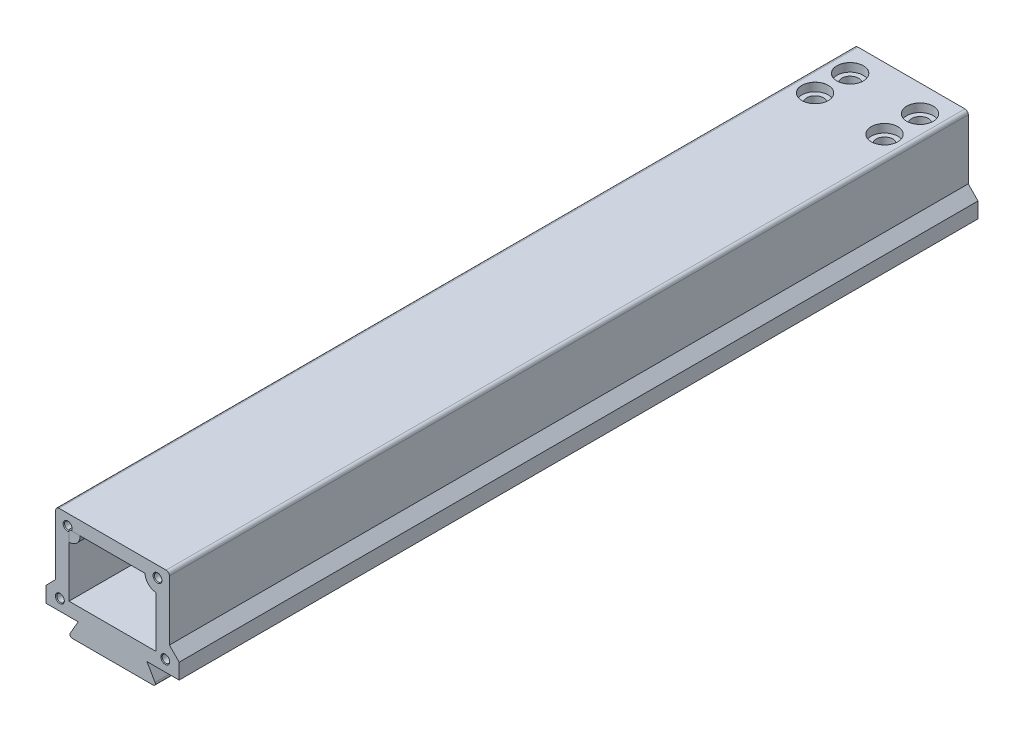
SolidWorks part; units mm, degrees
ref_plane "Front Plane" through (0, 0, 0) normal (0, 0, 1) x (1, 0, 0)
ref_plane "Top Plane" through (0, 0, 0) normal (0, 1, 0) x (1, 0, 0)
ref_plane "Right Plane" through (0, 0, 0) normal (1, 0, 0) x (0, 0, -1)
sketch "Sketch1" plane through (0, 0, 0) normal (0, 0, 1) x (1, 0, 0)
  line L0 (-39.9968, 0) -> (40, 0)
  line L1 (40, 0) -> (30.9933, 15.6)
  line L2 (30.9933, 15.6) -> (60, 15.6)
  line L3 (-39.9968, 0) -> (-30.9902, 15.6)
  line L4 (-30.9902, 15.6) -> (-60, 15.6)
  line L5 (-60, 15.6) -> (-60, 29.6)
  line L6 (-60, 29.6) -> (-51.25, 38.6)
  line L7 (-51.25, 38.6) -> (-51.25, 95.6)
  line L8 (60, 15.6) -> (60, 29.6)
  line L9 (60, 29.6) -> (51.25, 38.6)
  line L10 (51.25, 38.6) -> (51.25, 95.6)
  line L11 (-51.25, 95.6) -> (51.25, 95.6)
  dimension "D1" = 39.9968
  dimension "D2" = 40
  dimension "D3" = 15.6
  dimension "D4" = 60
  dimension "D5" = 60
  dimension "D6" = 60
  dimension "D7" = 15.6
  dimension "D8" = 60
  dimension "D9" = 14
  dimension "D10" = 23
  dimension "D11" = 51.25
  dimension "D12" = 95.6
  dimension "D13" = 51.25
extrude "Boss-Extrude1" add sketch "Sketch1" along normal blind 720
sketch "Sketch2" plane through (0, 0, 0) normal (0, 0, -1) x (-1, 0, 0)
  line L0 (60, 15.6) -> (30.9902, 15.6) construction
  line L1 (-40, 0) -> (40.8832, 0)
  line L2 (-40, 0) -> (-40, 15.6)
  line L3 (-40, 15.6) -> (40.8832, 15.6)
  line L4 (40.8832, 0) -> (40.8832, 15.6)
extrude "Cut-Extrude1" cut sketch "Sketch2" against normal blind 80
hole_wizard "CBORE for M12 Hex Head Bolt1" positions "3DSketch3" profile "Sketch6" counterbore size "M12" standard "ISO" end condition through all
sketch3d "3DSketch3"
  line L0 (51.25, 95.6, 0) -> (-51.25, 95.6, 0) construction
  line L1 (51.25, 95.6, 720) -> (51.25, 95.6, 0) construction
  point P0 (31.75, 95.6, 24)
  point P2 (-31.25, 95.6, 24)
  dimension "D1" = 24
  dimension "D2" = 19.5
  dimension "D3" = 24
  dimension "D4" = 63
sketch "Sketch6" plane through (31.75, 95.6, 24) normal (1, 0, 0) x (0, 0, 1)
  line L0 (0, 0) -> (0, 95.6)
  line L1 (0, 95.6) -> (7.5, 95.6)
  line L3 (7.5, 95.6) -> (7.5, 7.5)
  line L4 (11.8925, 7.5) -> (7.5, 7.5)
  line L5 (11.8925, 7.5) -> (11.8925, 0.025)
  line L6 (11.8925, 0.025) -> (11.9175, 0)
  line L7 (11.9175, 0) -> (0, 0)
  line L8 (-11.8925, 0.025) -> (-11.9175, 0) construction
  line L11 (0, -6.35) -> (0, 107.95) construction
  dimension "Thru Hole Dia." = 15
  dimension "Thru Hole Depth" = 95.6
  dimension "C'Bore Dia." = 23.785
  dimension "C'Bore Depth" = 7.5
  dimension "Near C'Sink Dia." = 23.835
  dimension "Near C'Sink Angle" = 90
hole_wizard "CBORE for M12 Hex Head Bolt2" positions "3DSketch4" profile "Sketch7" counterbore size "M12" standard "ISO" end condition through all
sketch3d "3DSketch4"
  line L0 (-51.25, 95.6, 720) -> (-51.25, 95.6, 0) construction
  line L1 (51.25, 95.6, 720) -> (51.25, 95.6, 0) construction
  circle A0 centre (-31.25, 88.1, 24) radius 7.5 construction
  circle A2 centre (31.75, 95.6, 24) radius 11.9175 construction
  point P0 (31.75, 95.6, 56)
  point P2 (-31.75, 95.6, 55.1047)
  point P9 (-31.25, 95.6, 24)
  point P17 (31.75, 107.5175, 24)
  dimension "D1" = 19.5
  dimension "D2" = 32
  dimension "D3" = 19.5
  dimension "D4" = 32
sketch "Sketch7" plane through (31.75, 95.6, 56) normal (1, 0, 0) x (0, 0, 1)
  line L0 (0, 0) -> (0, 95.6)
  line L1 (0, 95.6) -> (7.5, 95.6)
  line L3 (7.5, 95.6) -> (7.5, 7.5)
  line L4 (11.8925, 7.5) -> (7.5, 7.5)
  line L5 (11.8925, 7.5) -> (11.8925, 0.025)
  line L6 (11.8925, 0.025) -> (11.9175, 0)
  line L7 (11.9175, 0) -> (0, 0)
  line L8 (-11.8925, 0.025) -> (-11.9175, 0) construction
  line L11 (0, -6.35) -> (0, 107.95) construction
  dimension "Thru Hole Dia." = 15
  dimension "Thru Hole Depth" = 95.6
  dimension "C'Bore Dia." = 23.785
  dimension "C'Bore Depth" = 7.5
  dimension "Near C'Sink Dia." = 23.835
  dimension "Near C'Sink Angle" = 90
sketch "Sketch8" plane through (0, 0, 720) normal (0, 0, 1) x (1, 0, 0)
  line L0 (51.25, 95.6) -> (-51.25, 95.6) construction
  line L1 (-39.25, 83.6) -> (39.25, 83.6)
  line L2 (-39.25, 83.6) -> (-39.25, 27.6)
  line L3 (-39.25, 27.6) -> (39.25, 27.6)
  line L4 (39.25, 83.6) -> (39.25, 27.6)
  line L5 (30.9933, 15.6) -> (60, 15.6) construction
  line L6 (-51.25, 95.6) -> (-51.25, 38.6) construction
  line L7 (51.25, 38.6) -> (51.25, 95.6) construction
  dimension "D1" = 12
  dimension "D2" = 12
  dimension "D3" = 12
  dimension "D4" = 12
extrude "Cut-Extrude2" cut sketch "Sketch8" against normal blind 640
sketch "Sketch9" plane through (0, 0, 80) normal (0, 0, 1) x (1, 0, 0)
  line L0 (39.25, 83.6) -> (-39.25, 83.6) construction
  line L1 (-21.25, 83.6) -> (21.25, 83.6)
  line L2 (-21.25, 83.6) -> (-21.25, 27.6)
  line L3 (-21.25, 27.6) -> (21.25, 27.6)
  line L4 (21.25, 83.6) -> (21.25, 27.6)
  line L5 (-39.25, 27.6) -> (39.25, 27.6) construction
  line L6 (-51.25, 95.6) -> (-51.25, 38.6) construction
  line L7 (51.25, 38.6) -> (51.25, 95.6) construction
  dimension "D1" = 30
  dimension "D2" = 30
extrude "Cut-Extrude3" cut sketch "Sketch9" against normal blind 90
sketch "Sketch12" plane through (0, 0, 720) normal (0, 0, 1) x (1, 0, 0)
  line L0 (39.25, 27.6) -> (39.25, 83.6) construction
  line L1 (39.25, 83.6) -> (-39.25, 83.6) construction
  line L2 (29.25, 83.6) -> (39.474, 83.824)
  line L3 (39.474, 83.824) -> (39.25, 73.6)
  arc A0 (39.25, 73.6) -> (29.25, 83.6) centre (39.474, 83.824) cw
  dimension "D1" = 10
  dimension "D2" = 10
extrude "Boss-Extrude3" add sketch "Sketch12" against normal blind 30
hole_wizard "M8 Tapped Hole1" positions "3DSketch6" profile "Sketch13" tap size "M8" standard "ISO"
sketch3d "3DSketch6"
  line L0 (51.25, 38.6, 720) -> (51.25, 95.6, 720) construction
  line L1 (51.25, 95.6, 720) -> (-51.25, 95.6, 720) construction
  line L2 (-51.25, 95.6, 720) -> (-51.25, 38.6, 720) construction
  point P0 (-40.5, 85.6, 720)
  point P2 (40.5, 85.6, 720)
  dimension "D1" = 10.75
  dimension "D2" = 10
  dimension "D3" = 10
  dimension "D4" = 10.75
sketch "Sketch13" plane through (-40.5, 85.6, 720) normal (1, 0, 0) x (0, -1, 0)
  line L0 (0, 0) -> (0, 21.7929)
  line L1 (0, 21.7929) -> (3.4, 19.75)
  line L2 (3.4, 19.75) -> (3.4, 0.625)
  line L3 (3.4, 0.625) -> (4.025, 0)
  line L5 (4.025, 0) -> (0, 0)
  line L6 (-3.4, 0.625) -> (-4.025, 0) construction
  line L10 (0, 21.7929) -> (-3.4, 19.75) construction
  line L11 (0, -6.35) -> (0, 107.95) construction
  dimension "Tap Drill Dia." = 6.8
  dimension "Tap Drill Depth" = 19.75
  dimension "Near C'Sink Dia." = 8.05
  dimension "Near C'Sink Angle" = 90
  dimension "Drill Angle" = 118
cosmetic thread "Hole Thread6"
cosmetic thread "Hole Thread7"
hole_wizard "M8 Tapped Hole2" positions "3DSketch7" profile "Sketch15" tap size "M8" standard "ISO"
sketch3d "3DSketch7"
  line L0 (-60, 15.6, 720) -> (-30.9902, 15.6, 720) construction
  line L1 (-60, 29.6, 720) -> (-60, 15.6, 720) construction
  line L2 (60, 15.6, 720) -> (60, 29.6, 720) construction
  line L3 (30.9933, 15.6, 720) -> (60, 15.6, 720) construction
  point P0 (-47.5, 25.6, 720)
  point P2 (47.5, 25.6, 720)
  dimension "D1" = 10
  dimension "D2" = 12.5
  dimension "D3" = 12.5
  dimension "D4" = 10
sketch "Sketch15" plane through (-47.5, 25.6, 720) normal (1, 0, 0) x (0, -1, 0)
  line L0 (0, 0) -> (0, 21.7929)
  line L1 (0, 21.7929) -> (3.4, 19.75)
  line L2 (3.4, 19.75) -> (3.4, 0.625)
  line L3 (3.4, 0.625) -> (4.025, 0)
  line L5 (4.025, 0) -> (0, 0)
  line L6 (-3.4, 0.625) -> (-4.025, 0) construction
  line L10 (0, 21.7929) -> (-3.4, 19.75) construction
  line L11 (0, -6.35) -> (0, 107.95) construction
  dimension "Tap Drill Dia." = 6.8
  dimension "Tap Drill Depth" = 19.75
  dimension "Near C'Sink Dia." = 8.05
  dimension "Near C'Sink Angle" = 90
  dimension "Drill Angle" = 118
cosmetic thread "Hole Thread3"
cosmetic thread "Hole Thread4"
sketch "Sketch16" plane through (0, 0, 0) normal (0, -1, 0) x (-1, 0, 0)
  line L0 (-40, -720) -> (-40, -80) construction
  line L1 (18, -659.3203) -> (-18, -659.3203)
  line L2 (18, -659.3203) -> (18, -219.3438)
  line L3 (18, -219.3438) -> (-18, -219.3438)
  line L4 (-18, -659.3203) -> (-18, -219.3438)
  dimension "D1" = 36
  dimension "D2" = 22
extrude "Cut-Extrude4" cut sketch "Sketch16" against normal blind 30
fillet "Fillet1" radius 15 1 edges at (-18, 13.8, 659.3203)
fillet "Fillet2" radius 15 1 edges at (18, 13.8, 659.3203)
fillet "Fillet3" radius 15 1 edges at (-18, 13.8, 219.3438)
fillet "Fillet4" radius 15 1 edges at (18, 13.8, 219.3438)
fillet "Fillet5" radius 3 1 edges at (51.25, 95.6, 360)
fillet "Fillet6" radius 3 1 edges at (-51.25, 95.6, 360)
fillet "Fillet7" radius 2 1 edges at (40, 0, 400)
fillet "Fillet8" radius 2 1 edges at (-39.9968, 0, 400)
sketch "Sketch17" plane through (0, 0, 720) normal (0, 0, 1) x (1, 0, 0)
  line L0 (-21.25, 83.6) -> (-39.25, 83.6) construction
  line L1 (-39.25, 83.6) -> (-39.25, 27.6) construction
  line L2 (-39.25, 73.6) -> (-39.25, 83.6)
  line L3 (-39.25, 83.6) -> (-29.25, 83.6)
  arc A1 (-29.25, 83.6) -> (-39.25, 73.6) centre (-39.25, 83.6) cw
  dimension "D1" = 10
  dimension "D2" = 10
extrude "Boss-Extrude4" add sketch "Sketch17" against normal blind 30 separate body
sketch "Sketch18" plane through (0, 0, 720) normal (0, 0, 1) x (1, 0, 0)
  line L0 (60, 15.6) -> (30.9933, 15.6)
